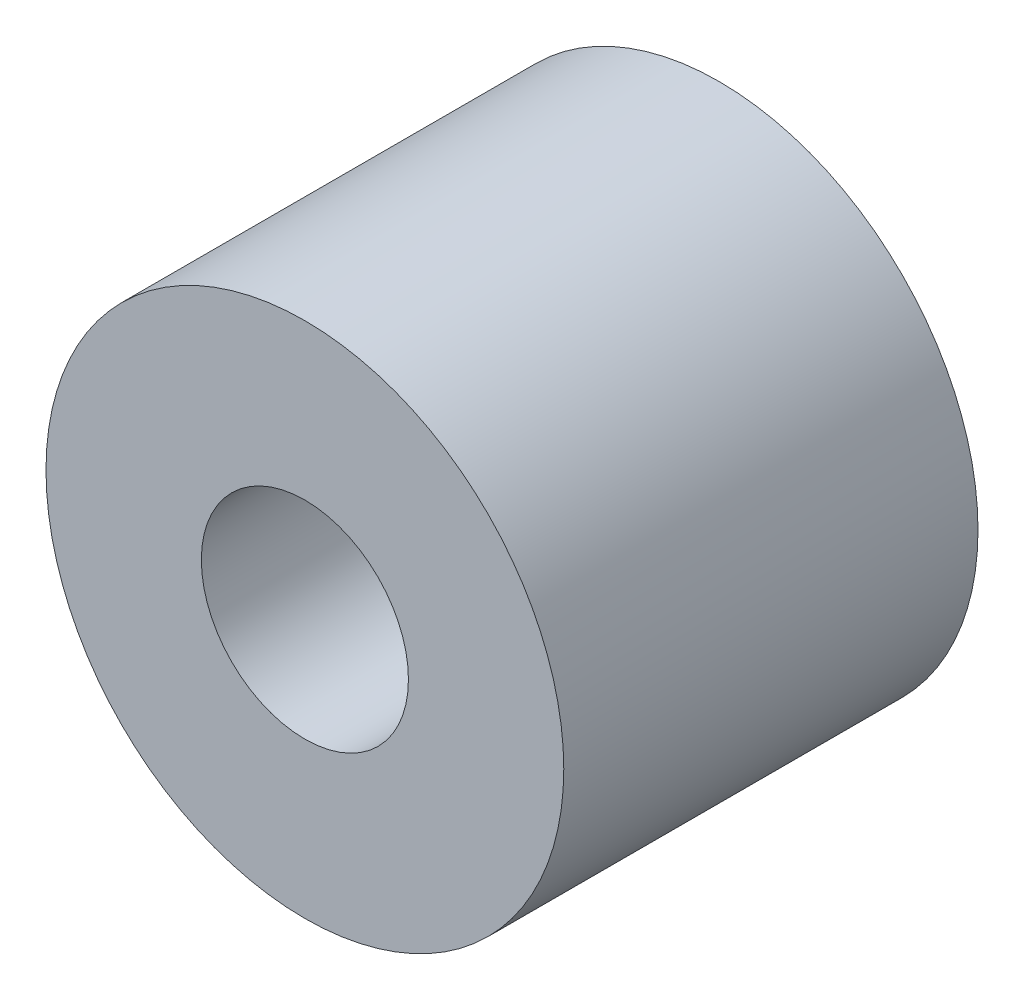
SolidWorks part; units mm, degrees
ref_plane "Front Plane" through (0, 0, 0) normal (0, 0, 1) x (1, 0, 0)
ref_plane "Top Plane" through (0, 0, 0) normal (0, 1, 0) x (1, 0, 0)
ref_plane "Right Plane" through (0, 0, 0) normal (1, 0, 0) x (0, 0, -1)
sketch "Sketch1" plane through (0, 0, 0) normal (0, 0, 1) x (1, 0, 0)
  circle A0 centre (0, 0) radius 1
  circle A1 centre (0, 0) radius 2.5
  dimension "D1" = 2
  dimension "D2" = 5
extrude "Boss-Extrude1" add sketch "Sketch1" along normal blind 4 contours A1 | A0
